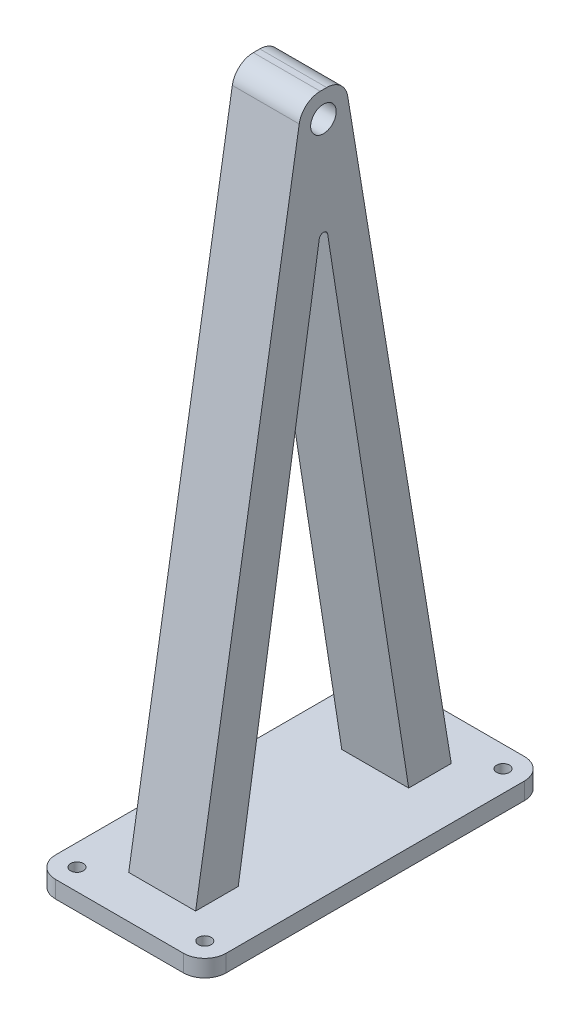
SolidWorks part; units mm, degrees
ref_plane "Front Plane" through (0, 0, 0) normal (0, 0, 1) x (1, 0, 0)
ref_plane "Top Plane" through (0, 0, 0) normal (0, 1, 0) x (1, 0, 0)
ref_plane "Right Plane" through (0, 0, 0) normal (1, 0, 0) x (0, 0, -1)
sketch "Sketch1" plane through (0, 0, 0) normal (0, 1, 0) x (1, 0, 0)
  line L1 (0, 0) -> (40, 0)
  line L2 (0, 0) -> (0, 80)
  line L3 (0, 80) -> (40, 80)
  line L4 (40, 0) -> (40, 80)
  circle A0 centre (5, 75) radius 1.54
  circle A1 centre (35, 75) radius 1.5
  circle A2 centre (5, 5) radius 1.5
  circle A3 centre (35, 5) radius 1.5
  dimension "D1" = 40
  dimension "D2" = 80
extrude "Boss-Extrude1" add sketch "Sketch1" along normal blind 4
fillet "Fillet1" radius 5 4 edges at (40, 2, -80) (40, 2, 0) (0, 2, 0) (0, 2, -80)
sketch "Sketch2" plane through (0, 4, 0) normal (0, 1, 0) x (1, 0, 0)
  line L1 (12.15, 70) -> (27.85, 70)
  line L2 (12.15, 70) -> (12.15, 10)
  line L3 (12.15, 10) -> (27.85, 10)
  line L4 (27.85, 70) -> (27.85, 10)
  line L6 (40, 5) -> (40, 75) construction
  dimension "D1" = 15.7
  dimension "D2" = 12.15
extrude "Boss-Extrude2" add sketch "Sketch2" along normal blind 152
sketch "Sketch3" plane through (40, 0, 0) normal (1, 0, 0) x (0, 0, -1)
  circle A0 centre (40, 150) radius 3
extrude "Cut-Extrude1" cut sketch "Sketch3" against normal blind 160
sketch "Sketch4" plane through (40, 0, 0) normal (1, 0, 0) x (0, 0, -1)
  line L0 (35, 156) -> (10, 4)
  line L1 (10, 156) -> (70, 156) construction
  line L2 (10, 4) -> (10, 156)
  line L3 (10, 156) -> (35, 156)
  line L4 (45, 156) -> (70, 4)
  line L5 (70, 4) -> (70, 156)
  line L6 (70, 156) -> (45, 156)
  dimension "D1" = 25
  dimension "D2" = 25
extrude "Cut-Extrude2" cut sketch "Sketch4" against normal blind 160
fillet "Fillet2" radius 5 2 edges at (20, 156, -45) (20, 156, -35)
sketch "Sketch5" plane through (27.85, 0, 0) normal (1, 0, 0) x (0, 0, -1)
  line L0 (20, 4) -> (40, 132.4523)
  line L1 (10, 4) -> (70, 4) construction
  line L2 (40, 132.4523) -> (60, 4)
  line L3 (60, 4) -> (20, 4)
  dimension "D1" = 130
  dimension "D2" = 130
  dimension "D3" = 10
  dimension "D4" = 10
  dimension "D5" = 40
extrude "Cut-Extrude3" cut sketch "Sketch5" against normal blind 160
fillet "Fillet3" radius 1 1 edges at (20, 132.4523, -40)
